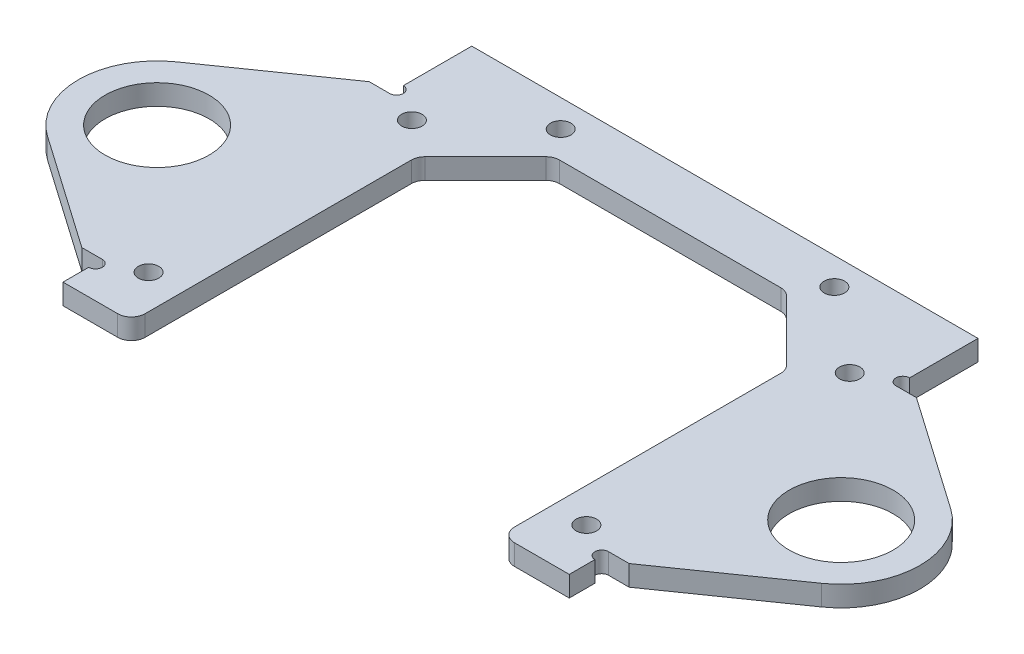
SolidWorks part; units mm, degrees
material "Thornel Mat VMA"
ref_plane "前视基准面" through (0, 0, 0) normal (0, 0, 1) x (1, 0, 0)
ref_plane "上视基准面" through (0, 0, 0) normal (0, 1, 0) x (1, 0, 0)
ref_plane "右视基准面" through (0, 0, 0) normal (1, 0, 0) x (0, 0, -1)
sketch "草图1" plane through (0, 0, 0) normal (0, 1, 0) x (1, 0, 0)
  line L0 (0, -1.65) -> (0, 1.65) construction
  line L3 (-37, 33) -> (-37, 21)
  line L11 (37, 33) -> (37, 21)
  line L12 (-37, 33) -> (37, 33)
  line L14 (-50, 0) -> (50, 0) construction
  line L15 (-32, 19.25) -> (32, 19.25) construction
  line L16 (-32, 19.25) -> (-32, -19.25) construction
  line L17 (-32, -19.25) -> (32, -19.25) construction
  line L18 (32, 19.25) -> (32, -19.25) construction
  line L28 (-37, -33) -> (37, -33)
  line L50 (-56.5805, 9.4312) -> (-40, 21)
  line L55 (-56.5805, -9.4312) -> (-40, -21)
  line L56 (-37, -21) -> (-37, -33)
  line L83 (37, -21) -> (37, -33)
  line L84 (56.5805, -9.4312) -> (40, -21)
  line L85 (56.5805, 9.4312) -> (40, 21)
  line L86 (-40, 21) -> (-37, 21)
  line L103 (-40, -21) -> (-37, -21)
  line L104 (40, -21) -> (37, -21)
  line L105 (40, 21) -> (37, 21)
  circle A0 centre (-50, 0) radius 7.6
  arc A2 (-56.5805, 9.4312) -> (-56.5805, -9.4312) centre (-50, 0) ccw
  circle A27 centre (50, 0) radius 7.6
  circle A28 centre (32, 19.25) radius 1.5
  circle A29 centre (32, -19.25) radius 1.5
  circle A32 centre (-32, -19.25) radius 1.5
  circle A35 centre (-32, 19.25) radius 1.5
  arc A37 (56.5805, 9.4312) -> (56.5805, -9.4312) centre (50, 0) cw
  circle A38 centre (-20, 29) radius 1.5
  circle A39 centre (20, 29) radius 1.5
  point P17 (-32, 0)
  dimension "D2" = 3
  dimension "D3" = 74
  dimension "D7" = 15.2
  dimension "D8" = 42
  dimension "D10" = 100
  dimension "D12" = 3
  dimension "D6" = 33
  dimension "D14" = 3
  dimension "D4" = 11.5
  dimension "D11" = 4
  dimension "D13" = 40
  dimension "D5" = 38.5
  dimension "D9" = 5
extrude "凸台-拉伸1" add sketch "草图1" along normal blind 3
sketch "草图2" plane through (0, 3, 0) normal (0, 1, 0) x (1, 0, 0)
  line L0 (-37, 33) -> (-37, 21) construction
  line L1 (-37, -21) -> (-37, -33) construction
  line L7 (0, -1.65) -> (0, 1.65) construction
  circle A21 centre (-37, 22) radius 1
  circle A22 centre (-37, -22) radius 1
  circle A23 centre (37, -22) radius 1
  circle A24 centre (37, 22) radius 1
extrude "切除-拉伸1" cut sketch "草图2" against normal through all
sketch "草图3" plane through (0, 3, 0) normal (0, 1, 0) x (1, 0, 0)
  line L13 (-27, -26.75) -> (-27, 25)
  line L14 (-27, 25) -> (27, 25)
  line L37 (-37, -33) -> (37, -33)
  line L38 (-37, -33) -> (-37, -26.75)
  line L39 (-37, -26.75) -> (-27, -26.75)
  line L41 (0, -1.65) -> (0, 1.65) construction
  line L43 (37, 33) -> (-37, 33) construction
  line L46 (37, -26.75) -> (27, -26.75)
  line L47 (37, -33) -> (37, -26.75)
  line L48 (27, -26.75) -> (27, 25)
  circle A0 centre (-32, 19.25) radius 1.5 construction
  circle A1 centre (-32, -19.25) radius 1.5 construction
  dimension "D1" = 8
  dimension "D2" = 5
  dimension "D3" = 7.5
extrude "切除-拉伸2" cut sketch "草图3" against normal through all
chamfer "倒角1" distance 10 angle 45 2 edges at (27, 1.5, -25) (-27, 1.5, -25)
fillet "圆角2" radius 2 6 edges at (27, 1.5, 26.75) (-27, 1.5, 26.75) (27, 1.5, -15) (17, 1.5, -25) (-27, 1.5, -15) (-17, 1.5, -25)
